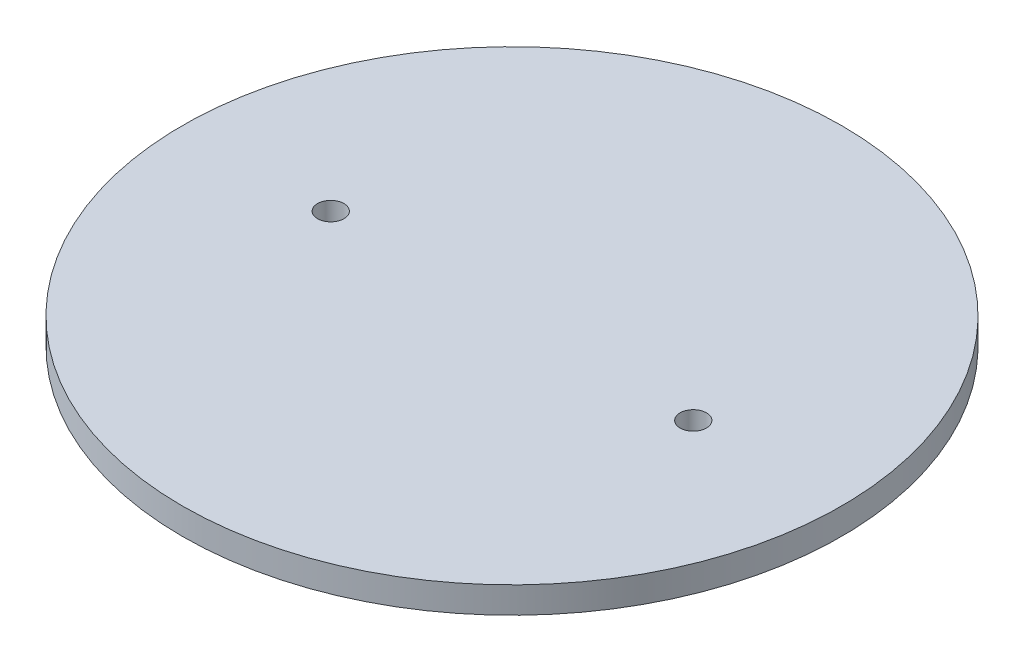
SolidWorks part; units mm, degrees
material "Balsa"
ref_plane "Front Plane" through (0, 0, 0) normal (0, 0, 1) x (1, 0, 0)
ref_plane "Top Plane" through (0, 0, 0) normal (0, 1, 0) x (1, 0, 0)
ref_plane "Right Plane" through (0, 0, 0) normal (1, 0, 0) x (0, 0, -1)
sketch "Sketch1" plane through (0, 0, 0) normal (0, 1, 0) x (1, 0, 0)
  line L0 (-50, 0) -> (50, 0) construction
  line L1 (0, 50) -> (0, -50) construction
  circle A0 centre (0, 0) radius 50
  circle A1 centre (-27.5, 0) radius 2
  circle A2 centre (27.5, 0) radius 2
  dimension "D1" = 55
extrude "Boss-Extrude1" add sketch "Sketch1" along normal blind 4
